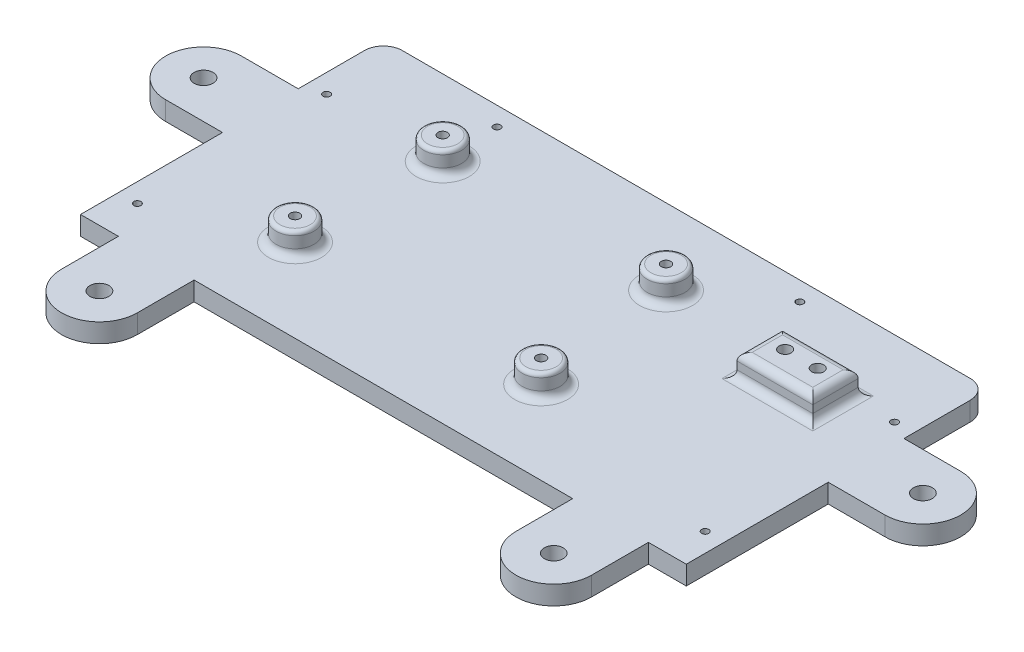
SolidWorks part; units mm, degrees
material "ABS"
ref_plane "Front Plane" through (0, 0, 0) normal (0, 0, 1) x (1, 0, 0)
ref_plane "Top Plane" through (0, 0, 0) normal (0, 1, 0) x (1, 0, 0)
ref_plane "Right Plane" through (0, 0, 0) normal (1, 0, 0) x (0, 0, -1)
sketch "Sketch1" plane through (0, 0, 0) normal (0, 1, 0) x (1, 0, 0)
  line L0 (101.6, 0) -> (101.6, 191.7492) construction
  line L1 (0, 0) -> (203.2, 0)
  line L2 (0, 0) -> (0, 95.25)
  line L3 (6.35, 101.6) -> (196.85, 101.6)
  line L4 (203.2, 0) -> (203.2, 95.25)
  circle A0 centre (6.35, 12.7) radius 1.1906
  circle A1 centre (196.85, 76.2) radius 1.1906
  circle A2 centre (6.35, 76.2) radius 1.1906
  circle A3 centre (44.45, 95.25) radius 1.1906
  circle A4 centre (146.05, 95.25) radius 1.1906
  circle A5 centre (196.85, 12.7) radius 1.1906
  arc A6 (196.85, 101.6) -> (203.2, 95.25) centre (196.85, 95.25) cw
  arc A7 (0, 95.25) -> (6.35, 101.6) centre (6.35, 95.25) cw
  point P9 (0, 101.6)
  point P24 (0, 101.6)
  dimension "D3" = 6.35
  dimension "D4" = 2.3813
  dimension "D1" = 101.6
  dimension "D2" = 203.2
  dimension "D5" = 6.35
  dimension "D6" = 12.7
  dimension "D7" = 63.5
  dimension "D8" = 6.35
  dimension "D9" = 57.15
  dimension "D10" = 101.6
extrude "Boss-Extrude1" add sketch "Sketch1" along normal blind 6.35
sketch "Sketch2" plane through (0, 6.35, 0) normal (0, 1, 0) x (1, 0, 0)
  line L0 (0, 0) -> (203.2, 0) construction
  circle A0 centre (45.2951, 76.2) radius 6.35
  circle A1 centre (120.2251, 76.2) radius 6.35
  circle A2 centre (44.0251, 27.94) radius 6.35
  circle A3 centre (126.5751, 27.94) radius 6.35
  dimension "D1" = 12.7
  dimension "D2" = 74.93
  dimension "D3" = 48.26
  dimension "D4" = 1.27
  dimension "D5" = 82.55
  dimension "D6" = 27.94
extrude "Boss-Extrude2" add sketch "Sketch2" along normal blind 7.62
fillet "Fillet1" radius 2.54 4 edges at (126.5751, 6.35, -34.29) (120.2251, 6.35, -82.55) (45.2951, 6.35, -82.55) (44.0251, 6.35, -34.29)
fillet "Fillet2" radius 1.27 4 edges at (44.0251, 13.97, -21.59) (45.2951, 13.97, -69.85) (126.5751, 13.97, -21.59) (120.2251, 13.97, -69.85)
sketch "Sketch5" plane through (0, 13.97, 0) normal (0, 1, 0) x (1, 0, 0)
  circle A1 centre (45.2951, 76.2) radius 1.5875
  circle A2 centre (120.2251, 76.2) radius 1.5875
  circle A3 centre (126.5751, 27.94) radius 1.5875
  circle A4 centre (44.0251, 27.94) radius 1.5875
  dimension "D1" = 3.175
extrude "Cut-Extrude1" cut sketch "Sketch5" against normal through all
sketch "Sketch6" plane through (0, 6.35, 0) normal (0, 1, 0) x (1, 0, 0)
  line L1 (0, 95.25) -> (0, 0) construction
  line L2 (0, 73.025) -> (-19.05, 73.025)
  line L3 (0, 73.025) -> (0, 47.625)
  line L4 (0, 47.625) -> (-19.05, 47.625)
  line L5 (0, 0) -> (203.2, 0) construction
  line L6 (12.7, 0) -> (38.1, 0)
  line L7 (12.7, 0) -> (12.7, -19.05)
  line L8 (165.1, 0) -> (101.6, 0) construction
  line L9 (38.1, 0) -> (38.1, -19.05)
  line L10 (203.2, 0) -> (203.2, 95.25) construction
  line L11 (190.5, 0) -> (165.1, 0)
  line L12 (190.5, 0) -> (190.5, -19.05)
  line L13 (101.6, 0) -> (38.1, 0) construction
  line L14 (165.1, 0) -> (165.1, -19.05)
  line L15 (203.2, 47.625) -> (222.25, 47.625)
  line L16 (203.2, 47.625) -> (203.2, 73.025)
  line L17 (203.2, 73.025) -> (222.25, 73.025)
  arc A0 (-19.05, 47.625) -> (-19.05, 73.025) centre (-19.05, 60.325) cw
  arc A1 (12.7, -19.05) -> (38.1, -19.05) centre (25.4, -19.05) ccw
  arc A2 (165.1, -19.05) -> (190.5, -19.05) centre (177.8, -19.05) ccw
  arc A3 (222.25, 47.625) -> (222.25, 73.025) centre (222.25, 60.325) ccw
  circle A4 centre (-19.05, 60.325) radius 3.175
  circle A5 centre (25.4, -19.05) radius 3.175
  circle A6 centre (177.8, -19.05) radius 3.175
  circle A7 centre (222.25, 60.325) radius 3.175
  point P30 (101.6, 0)
  dimension "D3" = 6.35
  dimension "D1" = 19.05
  dimension "D2" = 25.4
  dimension "D4" = 152.4
  dimension "D5" = 60.325
extrude "Boss-Extrude3" add sketch "Sketch6" against normal up to surface (6.35 mm away) up to face at (44.0251, 0, -26.3525)
sketch "Sketch7" plane through (0, 6.35, 0) normal (0, 1, 0) x (1, 0, 0)
  line L1 (183.1893, 77.6931) -> (157.7893, 77.6931)
  line L2 (183.1893, 77.6931) -> (183.1893, 62.4531)
  line L3 (183.1893, 62.4531) -> (157.7893, 62.4531)
  line L4 (157.7893, 77.6931) -> (157.7893, 62.4531)
  dimension "D1" = 25.4
  dimension "D5" = 15.24
extrude "Boss-Extrude4" add sketch "Sketch7" along normal up to surface (7.62 mm away) up to face at (120.2251, 13.97, -74.6125)
sketch "Sketch9" plane through (0, 13.97, 0) normal (0, 1, 0) x (1, 0, 0)
  line L0 (183.1893, 77.6931) -> (157.7893, 77.6931) construction
  line L1 (175.9503, 71.3431) -> (165.0283, 71.3431) construction
  line L2 (170.4893, 71.3431) -> (170.4893, 77.6931) construction
  circle A0 centre (175.9503, 71.3431) radius 2.032
  circle A1 centre (165.0283, 71.3431) radius 2.032
  dimension "D2" = 4.064
  dimension "D1" = 6.35
  dimension "D3" = 10.922
extrude "Cut-Extrude2" cut sketch "Sketch9" against normal through all
fillet "Fillet3" radius 2.54 8 edges at (183.1893, 6.35, -70.0731) (170.4893, 6.35, -62.4531) (157.7893, 6.35, -70.0731) (170.4893, 6.35, -77.6931) (157.7893, 13.97, -70.0731) (170.4893, 13.97, -62.4531) (183.1893, 13.97, -70.0731) (170.4893, 13.97, -77.6931)
